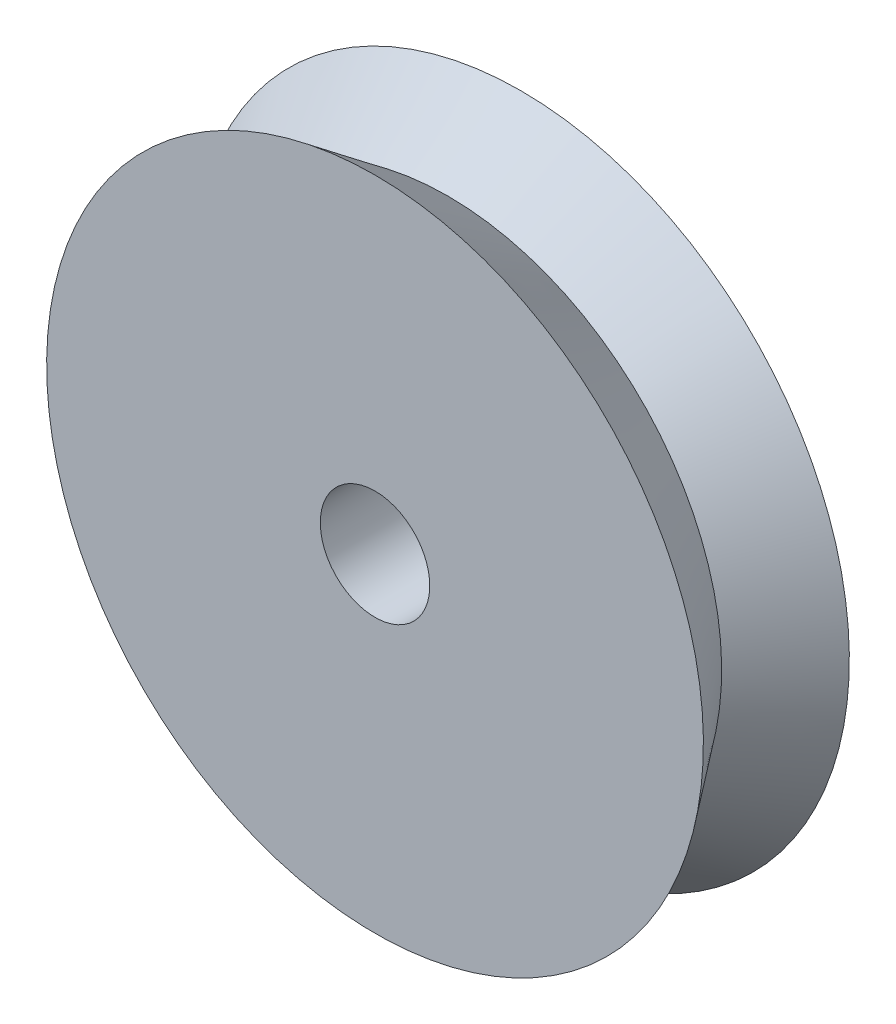
SolidWorks part; units mm, degrees
material "Настроенная пользователем пластмасса"
ref_plane "Спереди" through (0, 0, 0) normal (0, 0, 1) x (1, 0, 0)
ref_plane "Сверху" through (0, 0, 0) normal (0, 1, 0) x (1, 0, 0)
ref_plane "Справа" through (0, 0, 0) normal (1, 0, 0) x (0, 0, -1)
ref_plane "Плоскость4" through (0, 0, 0) normal (0, -1, 0) x (1, 0, 0)
sketch "Эскиз1" plane through (0, 0, 0) normal (0, -1, 0) x (1, 0, 0)
  line L0 (7.5, 2) -> (9, 4)
  line L1 (9, 4) -> (1.5, 4)
  line L2 (1.5, 4) -> (1.5, 0)
  line L3 (1.5, 0) -> (9, 0)
  line L4 (9, 0) -> (7.5, 2)
  line L5 (0, 4) -> (0, 0) construction
revolve "Повернуть1" add sketch "Эскиз1" angle 360 about L5
